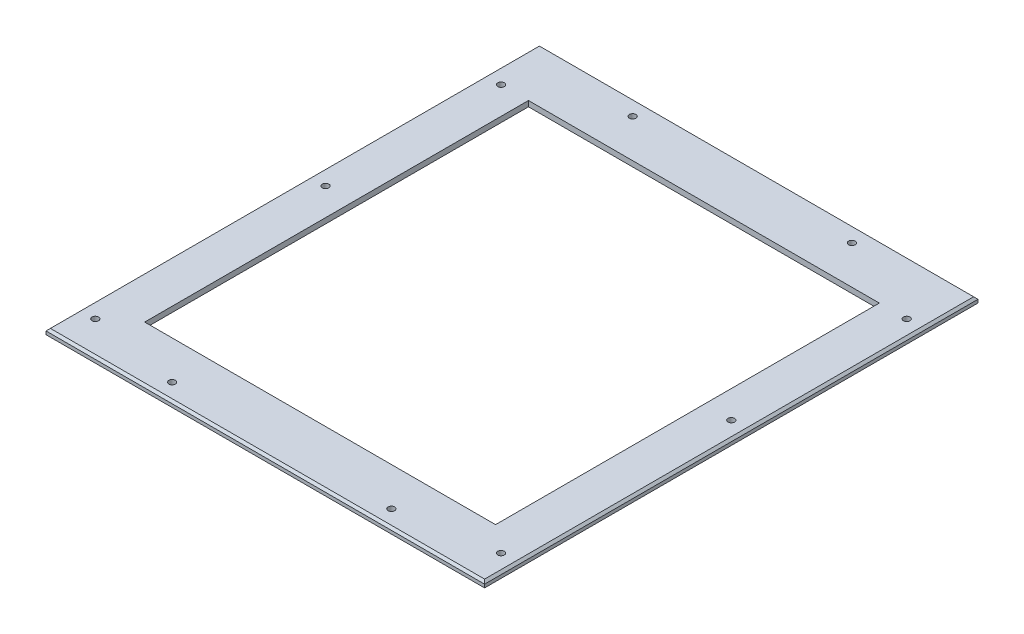
SolidWorks part; units mm, degrees
ref_plane "Alzado" through (0, 0, 0) normal (0, 0, 1) x (1, 0, 0)
ref_plane "Planta" through (0, 0, 0) normal (0, 1, 0) x (1, 0, 0)
ref_plane "Vista lateral" through (0, 0, 0) normal (1, 0, 0) x (0, 0, -1)
sketch "Croquis1" plane through (0, 0, 0) normal (0, 1, 0) x (1, 0, 0)
  line L1 (-172.8958, 182.928) -> (227.1042, 182.928)
  line L2 (-172.8958, 182.928) -> (-172.8958, -267.072)
  line L3 (-172.8958, -267.072) -> (227.1042, -267.072)
  line L4 (227.1042, 182.928) -> (227.1042, -267.072)
  line L6 (-132.8958, -217.072) -> (187.1042, -217.072)
  line L7 (-132.8958, -217.072) -> (-132.8958, 132.928)
  line L8 (-132.8958, 132.928) -> (187.1042, 132.928)
  line L9 (187.1042, -217.072) -> (187.1042, 132.928)
  circle A0 centre (-157.8958, 132.928) radius 3
  circle A1 centre (-157.8958, -237.072) radius 3
  circle A2 centre (212.1042, -237.072) radius 3
  circle A3 centre (212.1042, 132.928) radius 3
  circle A4 centre (-157.8958, -27.072) radius 3
  circle A5 centre (212.1042, -27.072) radius 3
  circle A6 centre (-72.8958, 167.928) radius 3
  circle A7 centre (127.1042, 167.928) radius 3
  circle A8 centre (127.1042, -252.072) radius 3
  circle A9 centre (-72.8958, -252.072) radius 3
  point P20 (27.1042, -42.072)
  dimension "D3" = 6
  dimension "D4" = 6
  dimension "D5" = 6
  dimension "D6" = 6
  dimension "D7" = 6
  dimension "D8" = 6
  dimension "D14" = 6
  dimension "D15" = 6
  dimension "D1" = 400
  dimension "D2" = 450
  dimension "D9" = 50
  dimension "D10" = 30
  dimension "D11" = 160
  dimension "D12" = 15
  dimension "D13" = 15
  dimension "D16" = 100
  dimension "D17" = 100
  dimension "D18" = 15
  dimension "D19" = 40
  dimension "D20" = 40
  dimension "D21" = 50
  dimension "D22" = 50
extrude "Saliente-Extruir1" add sketch "Croquis1" along normal blind 5
chamfer "Chaflán1" distance 2 angle 45 4 edges at (227.1042, 5, 42.072) (27.1042, 5, -182.928) (-172.8958, 5, 42.072) (27.1042, 5, 267.072)
